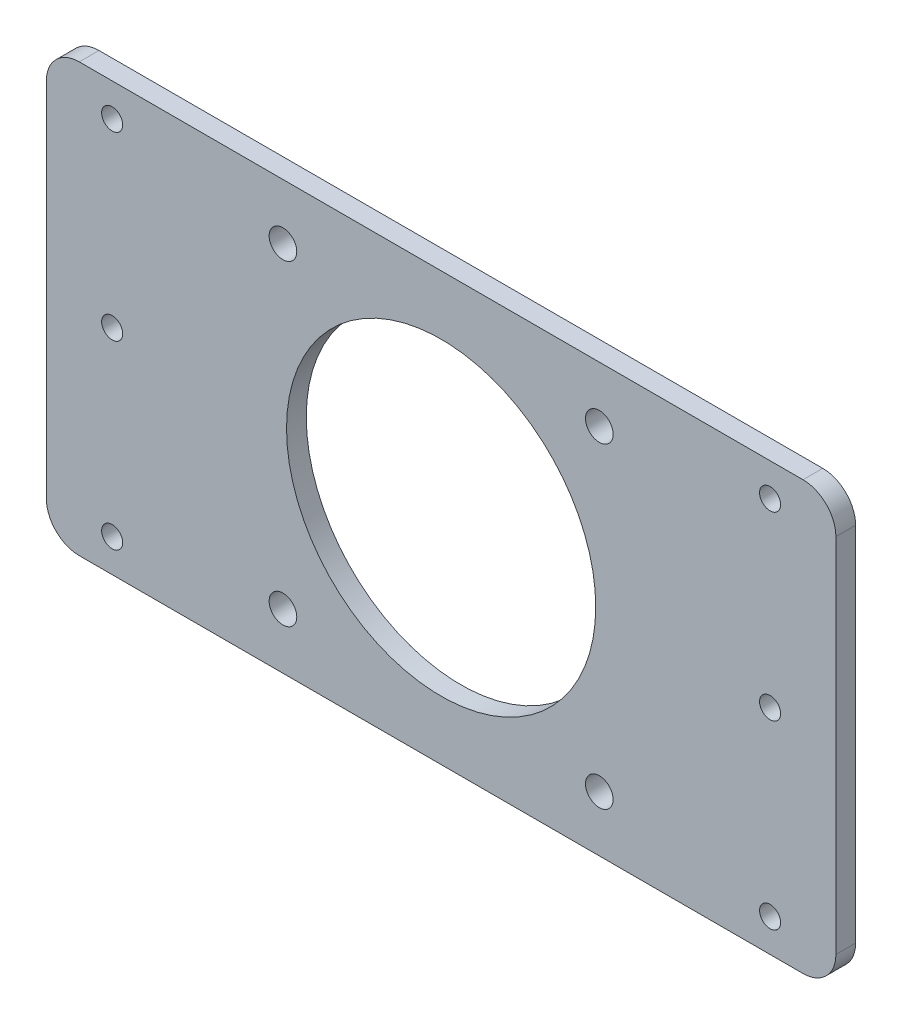
SolidWorks part; units mm, degrees
ref_plane "前视基准面" through (0, 0, 0) normal (0, 0, 1) x (1, 0, 0)
ref_plane "上视基准面" through (0, 0, 0) normal (0, 1, 0) x (1, 0, 0)
ref_plane "右视基准面" through (0, 0, 0) normal (1, 0, 0) x (0, 0, -1)
other "Configuration Table"
sketch "草图1" plane through (0, 0, 0) normal (0, 0, 1) x (1, 0, 0)
  line L1 (0, 0) -> (120, 0)
  line L2 (0, 0) -> (0, -65)
  line L3 (0, -65) -> (120, -65)
  line L4 (120, 0) -> (120, -65)
  dimension "D1" = 65
  dimension "D2" = 120
extrude "凸台-拉伸1" add sketch "草图1" along normal blind 3
sketch "草图2" plane through (0, 0, 3) normal (0, 0, 1) x (1, 0, 0)
  line L0 (10, 0) -> (10, -65) construction
  line L1 (120, 0) -> (0, 0) construction
  line L2 (0, -65) -> (120, -65) construction
  line L3 (0, 0) -> (0, -65) construction
  line L4 (60, 0) -> (60, -65) construction
  line L5 (110, 0) -> (110, -65) construction
  circle A0 centre (10, -5) radius 1.6
  circle A1 centre (10, -32.5) radius 1.6
  circle A2 centre (10, -60) radius 1.6
  circle A3 centre (110, -60) radius 1.6
  circle A4 centre (110, -32.5) radius 1.6
  circle A5 centre (110, -5) radius 1.6
  dimension "D2" = 3.2
  dimension "D3" = 5
  dimension "D4" = 5
  dimension "D1" = 10
extrude "切除-拉伸1" cut sketch "草图2" against normal through all
fillet "圆角1" radius 5 4 edges at (120, 0, 1.5) (120, -65, 1.5) (0, -65, 1.5) (0, 0, 1.5)
sketch "草图3" plane through (0, 0, 3) normal (0, 0, 1) x (1, 0, 0)
  line L0 (10, -32.5) -> (110, -32.5) construction
  circle A0 centre (60, -32.5) radius 23.5
  dimension "D1" = 47
extrude "切除-拉伸2" cut sketch "草图3" against normal blind 10
sketch "草图4" plane through (0, 0, 3) normal (0, 0, 1) x (1, 0, 0)
  line L0 (60, -32.5) -> (120, -32.5) construction
  line L1 (120, -60) -> (120, -5) construction
  line L2 (60, -32.5) -> (100.3033, 7.8033) construction
  circle A0 centre (60, -32.5) radius 34 construction
  circle A1 centre (84.0416, -8.4584) radius 2.1
  circle A2 centre (84.0416, -56.5416) radius 2.1
  circle A3 centre (35.9584, -56.5416) radius 2.1
  circle A4 centre (35.9584, -8.4584) radius 2.1
  dimension "D1" = 68
  dimension "D3" = 4.2
  dimension "D2" = 45
  dimension "D4" = 4
extrude "切除-拉伸3" cut sketch "草图4" against normal mid plane 10
